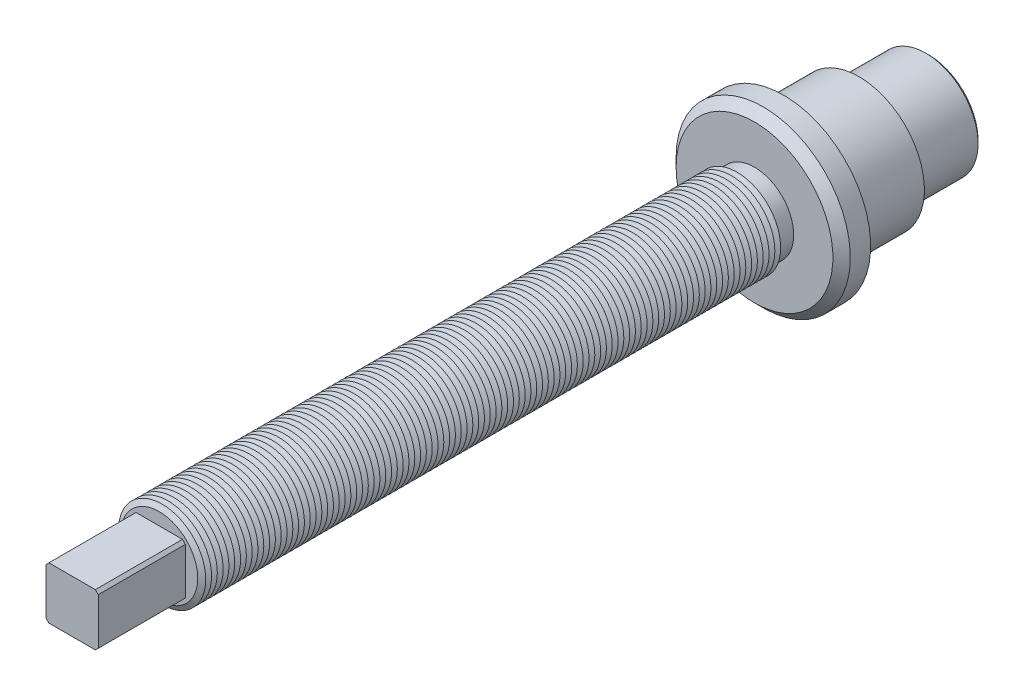
SolidWorks part; units mm, degrees
extrude "基体-拉伸" add sketch "草图1" against normal blind 230
sketch "草图1" plane through (0, 0, 0) normal (0, 0, 1) x (1, 0, 0)
  circle A0 centre (0, 0) radius 15
  dimension "D1" = 30
cosmetic thread "装饰螺纹线1" parameters "D2"=27.7778
material "钢"
ref_plane "前视" through (0, 0, 0) normal (0, 0, 1) x (1, 0, 0)
ref_plane "上视" through (0, 0, 0) normal (0, 1, 0) x (1, 0, 0)
ref_plane "右视" through (0, 0, 0) normal (1, 0, 0) x (0, 0, -1)
sketch "尺寸草图" plane through (0, 0, 0) normal (1, 0, 0) x (0, 0, -1)
  line L0 (0, 0) -> (230, 0) construction
  point P3 (11.5003, 0)
  point P4 (41.5003, 0)
  point P5 (38.2714, 0)
  point P6 (40.2714, 0)
  dimension "l" = 230
  dimension "d" = 30
  dimension "P" = 2
sketch "草图2" plane through (0, 0, 0) normal (1, 0, 0) x (0, 0, -1)
  line L0 (229, 15) -> (231, 15)
  line L1 (231, 15) -> (230, 13.268)
  line L2 (230, 13.268) -> (229, 15)
  line L3 (230, 15) -> (0, 15) construction
  line L4 (230, -15) -> (230, 15) construction
  line L5 (-103.3238, 0) -> (-94.9639, 0) construction
  line L6 (0, 0) -> (230, 0) construction
  dimension "D1" = 60
  dimension "D2" = 60
  dimension "D3" = 1.732
revolve "螺纹切除" cut sketch "草图2" angle 360 about L5
pattern_linear "左螺纹阵列" count 116 spacing 2 along (0, 0, 1) of "螺纹切除"
sketch "草图3" plane through (0, 0, -230) normal (0, 0, -1) x (-1, 0, 0)
  circle A0 centre (0, 0) radius 13.5
  dimension "D1" = 27
extrude "凸台-拉伸1" add sketch "草图3" along normal blind 5
sketch "草图4" plane through (0, 0, -235) normal (0, 0, -1) x (-1, 0, 0)
  circle A0 centre (0, 0) radius 30
  dimension "D1" = 60
extrude "凸台-拉伸2" add sketch "草图4" along normal blind 10
sketch "草图5" plane through (0, 0, -245) normal (0, 0, -1) x (-1, 0, 0)
  circle A0 centre (0, 0) radius 22.5
  dimension "D1" = 45
extrude "凸台-拉伸3" add sketch "草图5" along normal blind 50
chamfer "倒角1" distance 3 angle 45 1 edges at (-30, 0, -235)
sketch "草图6" plane through (0, 0, 0) normal (0, 0, 1) x (1, 0, 0)
  line L0 (0, 9) -> (0, -9) construction
  line L1 (-9, 9) -> (9, 9)
  line L2 (-9, 9) -> (-9, -9)
  line L3 (-9, -9) -> (9, -9)
  line L4 (9, 9) -> (9, -9)
  line L5 (-9, 0) -> (9, 0) construction
  circle A0 centre (0, 0) radius 16.5
  point P8 (0, 0)
  dimension "D3" = 33
  dimension "D1" = 18
  dimension "D2" = 18
extrude "切除-拉伸1" cut sketch "草图6" against normal blind 30
chamfer "倒角3" distance 1 angle 45 4 edges at (9, 9, -15) (9, -9, -15) (-9, -9, -15) (-9, 9, -15)
sketch "草图8" plane through (0, 0, -295) normal (0, 0, -1) x (-1, 0, 0)
  circle A0 centre (0, 0) radius 22.5
  circle A1 centre (0, 0) radius 18
  dimension "D1" = 36
  dimension "D2" = 45
extrude "切除-拉伸3" cut sketch "草图8" against normal blind 24
cosmetic thread "装饰螺纹线4" parameters "D2"=34.38
chamfer "倒角5" distance 1 angle 45 1 edges at (-18, 0, -295)
equation "\"D1@基体-拉伸\" = \"l@尺寸草图\""
equation "\"D1@草图1\" = \"d@尺寸草图\""
equation "\"D3@左螺纹阵列\" = \"P@尺寸草图\""
equation "\"D3@草图2\" = \"P@尺寸草图\" * 0.866"
equation "\"D1@左螺纹阵列\" = \"l@尺寸草图\" / \"P@尺寸草图\" + 1"
equation "\"D2@装饰螺纹线1\" = \"d@尺寸草图\" / 1.08"
